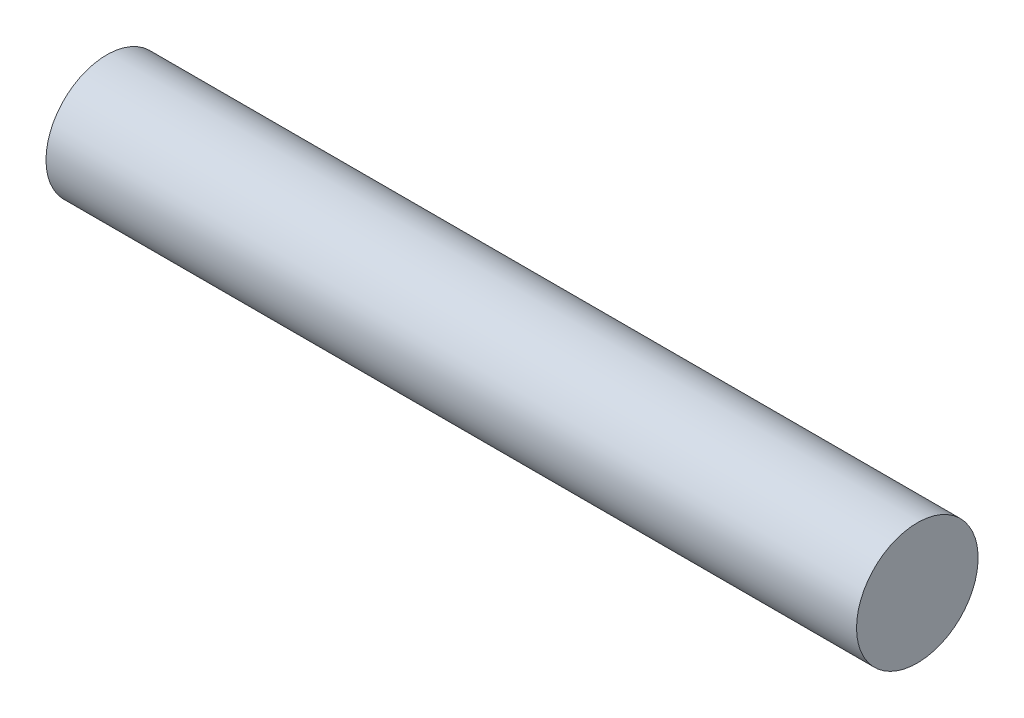
SolidWorks part; units mm, degrees
ref_plane "Front" through (0, 0, 0) normal (0, 0, 1) x (1, 0, 0)
ref_plane "Top" through (0, 0, 0) normal (0, 1, 0) x (1, 0, 0)
ref_plane "Right" through (0, 0, 0) normal (1, 0, 0) x (0, 0, -1)
sketch "Эскиз1" plane through (0, 0, 0) normal (0, 0, 1) x (1, 0, 0)
  line L0 (0, 0) -> (36.9802, 0) construction
  line L2 (0, 0) -> (20, 0)
  line L3 (0, 0) -> (0, 1.5)
  line L4 (0, 1.5) -> (20, 1.5)
  line L5 (20, 0) -> (20, 1.5)
  dimension "D1" = 20
  dimension "D2" = 1.5
revolve "Повернуть1" add sketch "Эскиз1" angle 360 about L0
